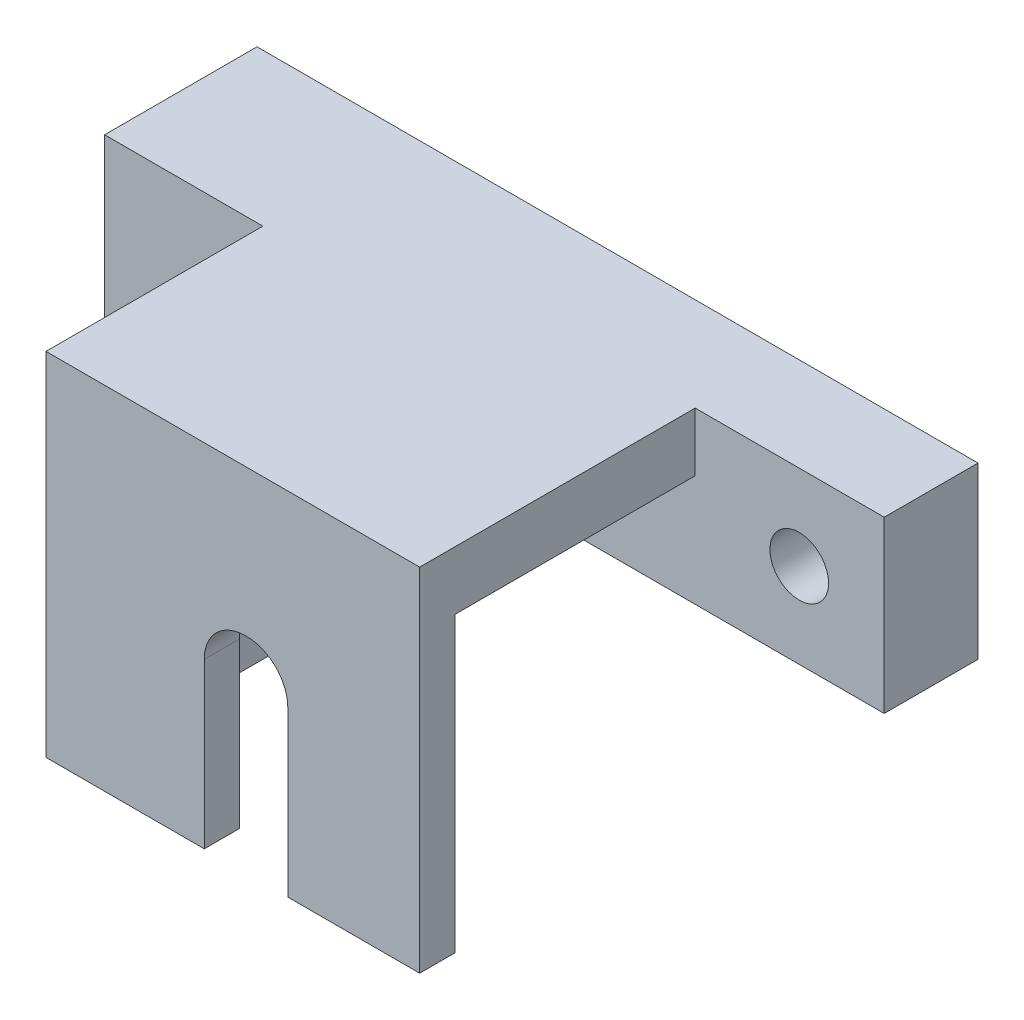
SolidWorks part; units mm, degrees
material "PET"
ref_plane "Ebene vorne" through (0, 0, 0) normal (0, 0, 1) x (1, 0, 0)
ref_plane "Ebene oben" through (0, 0, 0) normal (0, 1, 0) x (1, 0, 0)
ref_plane "Ebene rechts" through (0, 0, 0) normal (1, 0, 0) x (0, 0, -1)
sketch "Skizze1" plane through (0, 0, 0) normal (0, 0, 1) x (1, 0, 0)
  line L1 (0, 0) -> (24.6, 0)
  line L2 (0, 0) -> (0, 5.8)
  line L3 (0, 5.8) -> (24.6, 5.8)
  line L4 (24.6, 0) -> (24.6, 5.8)
  circle A0 centre (21.7, 2.9) radius 1
  dimension "D1" = 24.6
  dimension "D5" = 2
  dimension "D2" = 5.8
  dimension "D3" = 2.9
  dimension "D4" = 2.9
extrude "Aufsatz-Linear austragen1" add sketch "Skizze1" along normal blind 3.2
sketch "Skizze2" plane through (0, 0, 3.2) normal (0, 0, 1) x (1, 0, 0)
  line L1 (0, 5.8) -> (6.2, 5.8)
  line L2 (0, 5.8) -> (0, -6.2)
  line L3 (0, -6.2) -> (6.2, -6.2)
  line L4 (6.2, 5.8) -> (6.2, -6.2)
  dimension "D1" = 6.2
  dimension "D2" = 12
extrude "Aufsatz-Linear austragen2" add sketch "Skizze2" along normal blind 2
sketch "Skizze3" plane through (0, 0, 3.2) normal (0, 0, -1) x (-1, 0, 0)
  line L0 (-24.6, 5.8) -> (0, 5.8) construction
  circle A0 centre (-2.7, -3.1) radius 1
  circle A1 centre (-21.7, 2.9) radius 1 construction
  dimension "D1" = 19
  dimension "D2" = 2
  dimension "D3" = 8.9
extrude "Schnitt-Linear austragen1" cut sketch "Skizze3" against normal blind 2
sketch "Skizze4" plane through (0, 0, 3.2) normal (0, 0, 1) x (1, 0, 0)
  line L0 (6.2, 0) -> (24.6, 0) construction
  line L1 (6.2, 5.8) -> (10.8, 5.8)
  line L3 (6.2, 0) -> (10.8, 0)
  line L4 (10.8, 5.8) -> (10.8, 0)
  line L5 (6.2, 5.8) -> (0, 5.8) construction
  line L6 (6.2, -6.2) -> (5.4, -6.2)
  line L7 (6.2, -6.2) -> (6.2, 0)
  line L8 (6.2, 5.8) -> (5.4, 5.8)
  line L9 (5.4, -6.2) -> (5.4, 5.8)
  line L10 (6.2, 0) -> (6.2, 5.8) construction
  dimension "D1" = 0.8
  dimension "D2" = 4.6
extrude "Aufsatz-Linear austragen3" add sketch "Skizze4" along normal blind 8.2
sketch "Skizze5" plane through (0, 5.8, 0) normal (0, 1, 0) x (1, 0, 0)
  line L1 (5.4, -11.4) -> (10.8, -11.4)
  line L2 (5.4, -11.4) -> (5.4, -12.6)
  line L3 (5.4, -12.6) -> (10.8, -12.6)
  line L4 (10.8, -11.4) -> (10.8, -12.6)
  dimension "D1" = 1.2
extrude "Aufsatz-Linear austragen4" add sketch "Skizze5" against normal up to surface (12 mm away) up to face at (3.8667, -6.2, 6.6)
sketch "Skizze6" plane through (0, 0, 0) normal (0, -1, 0) x (1, 0, 0)
  line L1 (6.2, 3.2) -> (10.8, 3.2)
  line L2 (6.2, 3.2) -> (6.2, 11.4)
  line L3 (6.2, 11.4) -> (10.8, 11.4)
  line L4 (10.8, 3.2) -> (10.8, 11.4)
extrude "Schnitt-Linear austragen2" cut sketch "Skizze6" against normal blind 3.8
sketch "Skizze7" plane through (10.8, 0, 0) normal (1, 0, 0) x (0, 0, -1)
  line L0 (-12.6, -6.2) -> (-12.6, 5.8) construction
  line L1 (-3.2, 3.8) -> (-11.4, 3.8) construction
  line L2 (-3.2, 3.8) -> (-3.2, 5.8) construction
  line L3 (-12.6, 5.8) -> (-3.2, 5.8) construction
  line L4 (-12.6, -6.2) -> (-12.6, 5.8)
  line L5 (-3.2, 3.8) -> (-11.4, 3.8)
  line L6 (-3.2, 3.8) -> (-3.2, 5.8)
  line L7 (-12.6, 5.8) -> (-3.2, 5.8)
  line L8 (-12.6, 0.8) -> (-11.4, 0.8)
  line L9 (-11.4, -6.2) -> (-11.4, 3.8) construction
  line L10 (-11.4, -6.2) -> (-11.4, 3.8) construction
  line L11 (-11.4, -6.2) -> (-11.4, 3.8)
  line L12 (-12.6, 5.8) -> (-12.6, 0.8)
  line L13 (-12.6, 5.8) -> (-3.2, 5.8)
  line L14 (-3.2, 5.8) -> (-3.2, 3.8)
  line L15 (-3.2, 3.8) -> (-11.4, 3.8)
  line L16 (-11.4, 3.8) -> (-11.4, 0.8)
  line M3 (-11.4, -6.2) -> (-11.4, 3.8)
  line M4 (-11.4, 3.8) -> (-3.2, 3.8)
  line M5 (-3.2, 3.8) -> (-3.2, 5.8)
  line M6 (-3.2, 5.8) -> (-12.6, 5.8)
  line M7 (-12.6, 5.8) -> (-12.6, -6.2)
  dimension "D1" = 5
extrude "Aufsatz-Linear austragen5" add sketch "Skizze7" along normal blind 2.85 contours L8 M7 M3 M4 M5 M6
sketch "Skizze8" plane through (13.65, 0, 0) normal (1, 0, 0) x (0, 0, -1)
  line L0 (-3.2, 5.8) -> (-12.6, 5.8)
  line L1 (-12.6, 5.8) -> (-12.6, -6.2)
  line L2 (-12.6, -6.2) -> (-11.4, -6.2)
  line L3 (-11.4, -6.2) -> (-11.4, 3.8)
  line L4 (-11.4, 3.8) -> (-3.2, 3.8)
  line L5 (-3.2, 3.8) -> (-3.2, 5.8)
extrude "Aufsatz-Linear austragen6" add sketch "Skizze8" along normal blind 4.5
fillet "Verrundung1" radius 1.4 2 edges at (13.65, 0.8, 12) (10.8, 0.8, 12)
